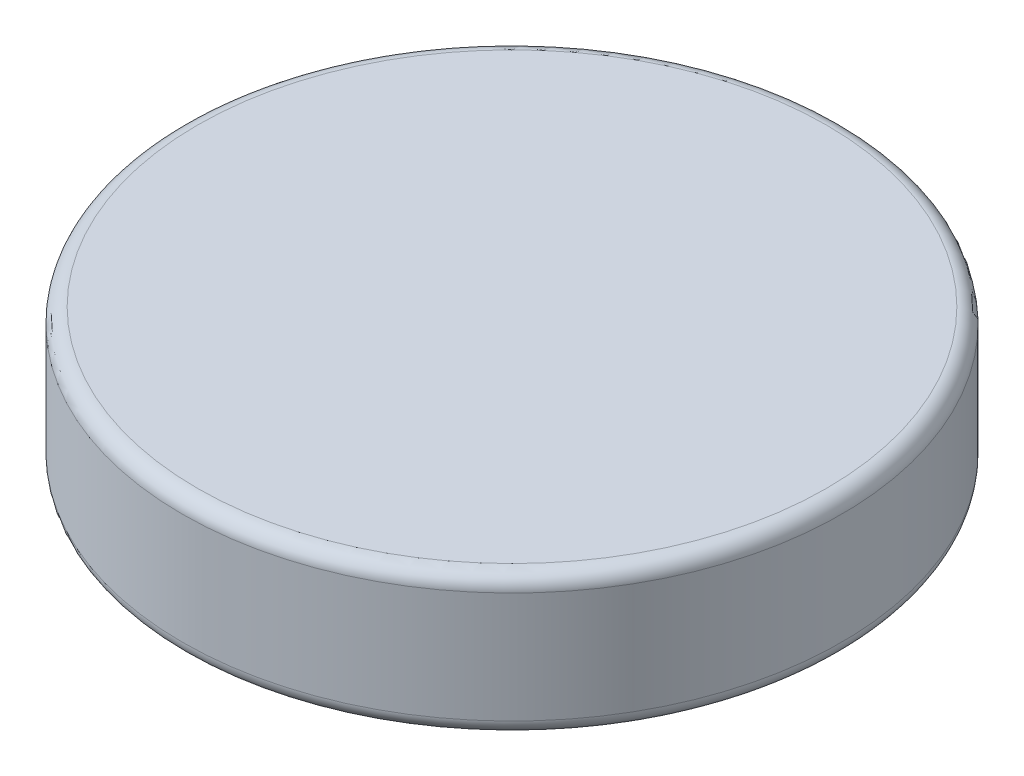
SolidWorks part; units mm, degrees
ref_plane "Front Plane" through (0, 0, 0) normal (0, 0, 1) x (1, 0, 0)
ref_plane "Top Plane" through (0, 0, 0) normal (0, 1, 0) x (1, 0, 0)
ref_plane "Right Plane" through (0, 0, 0) normal (1, 0, 0) x (0, 0, -1)
sketch "Sketch1" plane through (0, 0, 0) normal (0, 1, 0) x (1, 0, 0)
  circle A0 centre (0, 0) radius 11
  dimension "D1" = 22
extrude "Boss-Extrude1" add sketch "Sketch1" along normal mid plane 4.7
fillet "Fillet1" radius 0.5 2 edges at (0, -2.35, 11) (0, 2.35, 11)
